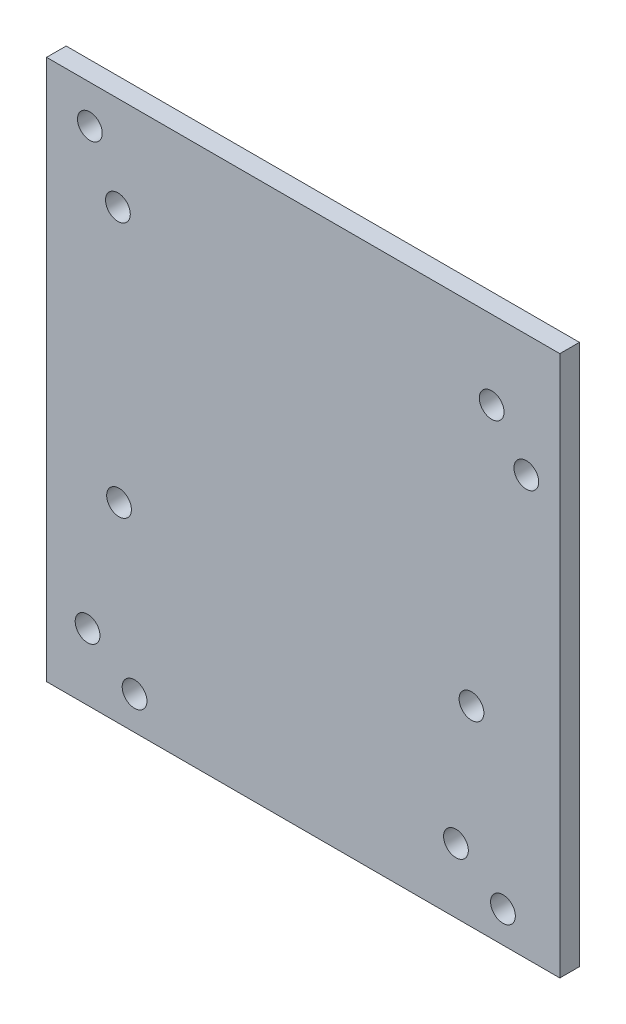
SolidWorks part; units mm, degrees
ref_plane "Front Plane" through (0, 0, 0) normal (0, 0, 1) x (1, 0, 0)
ref_plane "Top Plane" through (0, 0, 0) normal (0, 1, 0) x (1, 0, 0)
ref_plane "Right Plane" through (0, 0, 0) normal (1, 0, 0) x (0, 0, -1)
sketch "Sketch1" plane through (0, 0, 0) normal (0, 0, 1) x (1, 0, 0)
  line L0 (-570.3819, 236.4783) -> (-570.3819, 211.0783) construction
  line L5 (-570.3819, 211.0783) -> (-540.0489, 211.0783) construction
  line L6 (-540.0489, 211.0783) -> (-540.0489, 236.4783) construction
  line L7 (-540.0489, 236.4783) -> (-570.3819, 236.4783) construction
  line L8 (-532.8862, 362.9134) -> (-560.1463, 365.8966) construction
  line L9 (-560.1463, 365.8966) -> (-560.5461, 336.3644) construction
  line L10 (-560.5461, 336.3644) -> (-533.286, 333.3813) construction
  line L11 (-533.286, 333.3813) -> (-532.8862, 362.9134) construction
  line L12 (-659.3105, 377.0773) -> (-686.7338, 380.0783) construction
  line L13 (-686.7338, 380.0783) -> (-692.9825, 350.529) construction
  line L14 (-692.9825, 350.529) -> (-665.5591, 347.5279) construction
  line L15 (-665.5591, 347.5279) -> (-659.3105, 377.0773) construction
  line L16 (-660.6408, 211.0783) -> (-660.6408, 236.4783) construction
  line L17 (-660.6408, 236.4783) -> (-690.9738, 236.4783) construction
  line L18 (-690.9738, 236.4783) -> (-690.9738, 211.0783) construction
  line L19 (-690.9738, 211.0783) -> (-660.6408, 211.0783) construction
  line L20 (-570.3819, 236.4783) -> (-570.3819, 211.0783) construction
  line L21 (-570.3819, 211.0783) -> (-540.0489, 211.0783) construction
  line L22 (-540.0489, 211.0783) -> (-540.0489, 236.4783) construction
  line L23 (-540.0489, 236.4783) -> (-570.3819, 236.4783) construction
  line L24 (-532.8862, 362.9134) -> (-560.1463, 365.8966) construction
  line L25 (-560.1463, 365.8966) -> (-560.5461, 336.3644) construction
  line L26 (-560.5461, 336.3644) -> (-533.286, 333.3813) construction
  line L27 (-533.286, 333.3813) -> (-532.8862, 362.9134) construction
  line L28 (-659.3105, 377.0773) -> (-686.7338, 380.0783) construction
  line L29 (-686.7338, 380.0783) -> (-692.9825, 350.529) construction
  line L30 (-692.9825, 350.529) -> (-665.5591, 347.5279) construction
  line L31 (-665.5591, 347.5279) -> (-659.3105, 377.0773) construction
  line L32 (-660.6408, 211.0783) -> (-660.6408, 236.4783) construction
  line L33 (-660.6408, 236.4783) -> (-690.9738, 236.4783) construction
  line L34 (-690.9738, 236.4783) -> (-690.9738, 211.0783) construction
  line L35 (-690.9738, 211.0783) -> (-660.6408, 211.0783) construction
  line L36 (-686.7338, 380.0783) -> (-540.0489, 211.0783) construction
  line L37 (-690.9738, 211.0783) -> (-532.8862, 362.9134) construction
  line L39 (-696.1575, 207.9033) -> (-529.7112, 207.9033)
  line L40 (-696.1575, 207.9033) -> (-696.1575, 383.2533)
  line L41 (-696.1575, 383.2533) -> (-529.7112, 383.2533)
  line L42 (-529.7112, 207.9033) -> (-529.7112, 383.2533)
  line L43 (-696.1575, 207.9033) -> (-529.7112, 383.2533) construction
  line L44 (-696.1575, 383.2533) -> (-529.7112, 207.9033) construction
  circle A0 centre (-548.1569, 218.0633) radius 2.5273 construction
  circle A1 centre (-563.3969, 228.8583) radius 2.5273 construction
  circle A2 centre (-540.573, 343.7606) radius 2.5273 construction
  circle A3 centre (-551.816, 357.7668) radius 2.5273 construction
  circle A4 centre (-673.0254, 352.7515) radius 2.5273 construction
  circle A5 centre (-682.1218, 370.9328) radius 2.5273 construction
  circle A6 centre (-682.8658, 229.4933) radius 2.5273 construction
  circle A7 centre (-667.6258, 218.6983) radius 2.5273 construction
  circle A8 centre (-548.1569, 218.0633) radius 2.5273 construction
  circle A9 centre (-563.3969, 228.8583) radius 2.5273 construction
  circle A10 centre (-540.573, 343.7606) radius 2.5273 construction
  circle A11 centre (-551.816, 357.7668) radius 2.5273 construction
  circle A12 centre (-673.0254, 352.7515) radius 2.5273 construction
  circle A13 centre (-682.1218, 370.9328) radius 2.5273 construction
  circle A14 centre (-682.8658, 229.4933) radius 2.5273 construction
  circle A15 centre (-667.6258, 218.6983) radius 2.5273 construction
  circle A23 centre (-667.6258, 218.6983) radius 4.0127
  circle A24 centre (-682.8658, 229.4933) radius 4.0127
  circle A25 centre (-682.1218, 370.9328) radius 4.0127
  circle A26 centre (-673.0254, 352.7515) radius 4.0127
  circle A27 centre (-551.816, 357.7668) radius 4.0127
  circle A28 centre (-540.573, 343.7606) radius 4.0127
  circle A29 centre (-548.1569, 218.0633) radius 4.0127
  circle A30 centre (-563.3969, 228.8583) radius 4.0127
  circle A31 centre (-558.3616, 269.9726) radius 3 construction
  circle A32 centre (-672.6612, 269.9726) radius 3 construction
  circle A33 centre (-558.3616, 269.9726) radius 3 construction
  circle A34 centre (-672.6612, 269.9726) radius 3 construction
  circle A35 centre (-558.3616, 269.9726) radius 4.0132
  circle A36 centre (-672.6612, 269.9726) radius 4.0132
  point P1 (-608.6645, 290.1323)
  point P18 (-612.9344, 295.5783)
  dimension "D5" = 8.0254
  dimension "D6" = 8.0264
  dimension "D1" = 3.175
  dimension "D2" = 3.175
  dimension "D3" = 3.175
  dimension "D4" = 3.175
extrude "Boss-Extrude1" add sketch "Sketch1" along normal blind 6.35
move or copy body "Body-Move/Copy1" bodies to move or copy 102 parameters "D1"=0, "D2"=0, "D3"=0
